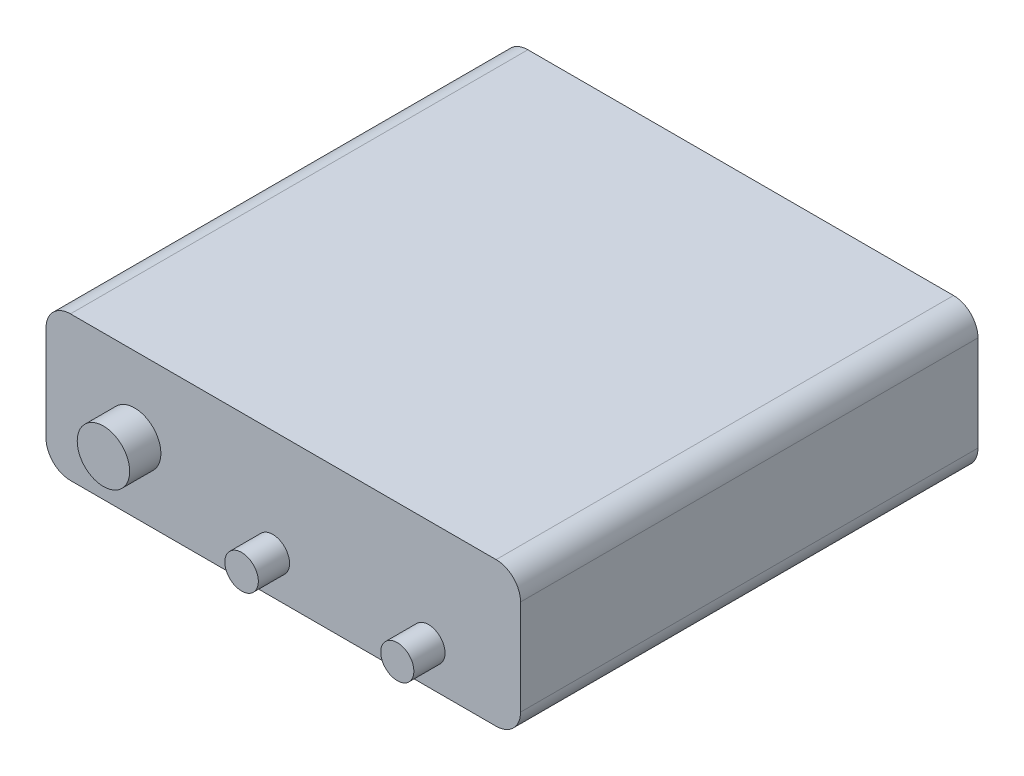
SolidWorks part; units mm, degrees
ref_plane "Front Plane" through (0, 0, 0) normal (0, 0, 1) x (1, 0, 0)
ref_plane "Top Plane" through (0, 0, 0) normal (0, 1, 0) x (1, 0, 0)
ref_plane "Right Plane" through (0, 0, 0) normal (1, 0, 0) x (0, 0, -1)
sketch "Sketch1" plane through (0, 0, 0) normal (0, 1, 0) x (1, 0, 0)
  line L1 (0, 0) -> (-197.104, 0)
  line L2 (0, 0) -> (0, -189.992)
  line L3 (0, -189.992) -> (-197.104, -189.992)
  line L4 (-197.104, 0) -> (-197.104, -189.992)
extrude "Boss-Extrude1" add sketch "Sketch1" along normal blind 59.944
fillet "Fillet1" radius 10.16 1 edges at (0, 59.944, 94.996)
fillet "Fillet2" radius 10.16 1 edges at (0, 0, 94.996)
fillet "Fillet3" radius 10.16 1 edges at (-197.104, 59.944, 94.996)
fillet "Fillet4" radius 10.16 1 edges at (-197.104, 0, 94.996)
sketch "Sketch2" plane through (0, 0, 189.992) normal (0, 0, 1) x (1, 0, 0)
  circle A0 centre (-160.2891, 28.5286) radius 10.8928
  circle A1 centre (-102.9103, 15.6747) radius 6.9567
  circle A2 centre (-38.2432, 15.6747) radius 6.8716
extrude "Boss-Extrude3" add sketch "Sketch2" along normal blind 12.954
